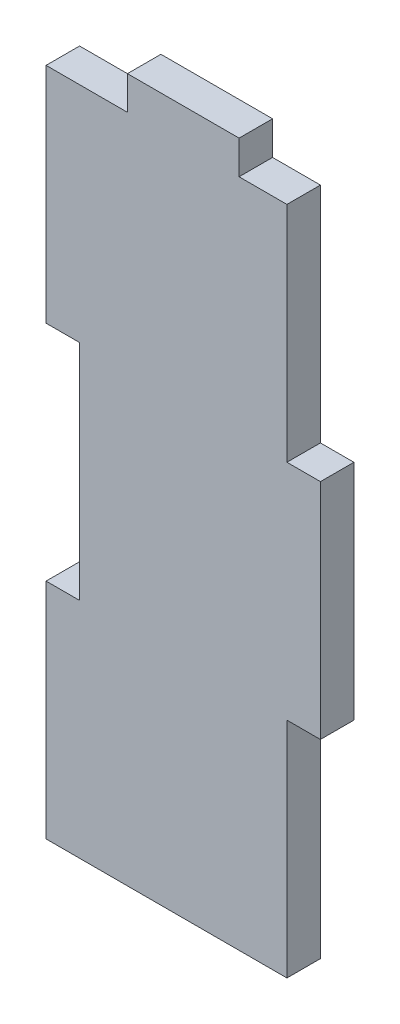
SolidWorks part; units mm, degrees
ref_plane "Front Plane" through (0, 0, 0) normal (0, 0, 1) x (1, 0, 0)
ref_plane "Top Plane" through (0, 0, 0) normal (0, 1, 0) x (1, 0, 0)
ref_plane "Right Plane" through (0, 0, 0) normal (1, 0, 0) x (0, 0, -1)
sketch "Sketch1" plane through (0, 0, 0) normal (0, 0, 1) x (1, 0, 0)
  line L0 (21.57, 0) -> (0, 0)
  line L1 (21.57, 20) -> (21.57, 0)
  line L2 (24.57, 20) -> (21.57, 20)
  line L3 (24.57, 40) -> (24.57, 20)
  line L4 (21.57, 40) -> (24.57, 40)
  line L5 (21.57, 60) -> (21.57, 40)
  line L6 (13.785, 60) -> (21.57, 60)
  line L7 (13.785, 63) -> (13.785, 60)
  line L8 (10.785, 63) -> (13.785, 63)
  line L9 (10.785, 60) -> (10.785, 63)
  line L10 (0, 60) -> (10.785, 60)
  line L11 (0, 40) -> (0, 60)
  line L12 (3, 40) -> (0, 40)
  line L13 (3, 20) -> (3, 40)
  line L14 (0, 20) -> (3, 20)
  line L15 (0, 0) -> (0, 20)
  dimension "D1" = 21.57
extrude "Plate_thickness_3mm" add sketch "Sketch1" along normal blind 3
sketch "草图1" plane through (0, 0, 3) normal (0, 0, 1) x (1, 0, 0)
  line L0 (21.57, 60) -> (13.785, 60) construction
  line L1 (7.285, 63) -> (17.285, 63)
  line L2 (7.285, 63) -> (7.285, 60)
  line L3 (7.285, 60) -> (17.285, 60)
  line L4 (17.285, 63) -> (17.285, 60)
  line L5 (7.285, 63) -> (17.285, 60) construction
  line L6 (7.285, 60) -> (17.285, 63) construction
  line L7 (12.285, 63) -> (12.285, 0)
  line L8 (13.785, 63) -> (10.785, 63) construction
  line L9 (0, 0) -> (21.57, 0) construction
  point P0 (12.285, 61.5)
  line M11 (21.57, 60) -> (13.785, 60)
  line M12 (13.785, 60) -> (13.785, 63)
  line M14 (10.785, 63) -> (10.785, 60)
  line M15 (10.785, 60) -> (0, 60)
  dimension "D1" = 10
  dimension "D2" = 5
  dimension "D3" = 3
extrude "凸台-拉伸2" add sketch "草图1" against normal up to surface (3 mm away) contours L1 L2 M15 M14 | L4 L1 M12 M11 up to face at (11.91, 37.875, 0)
